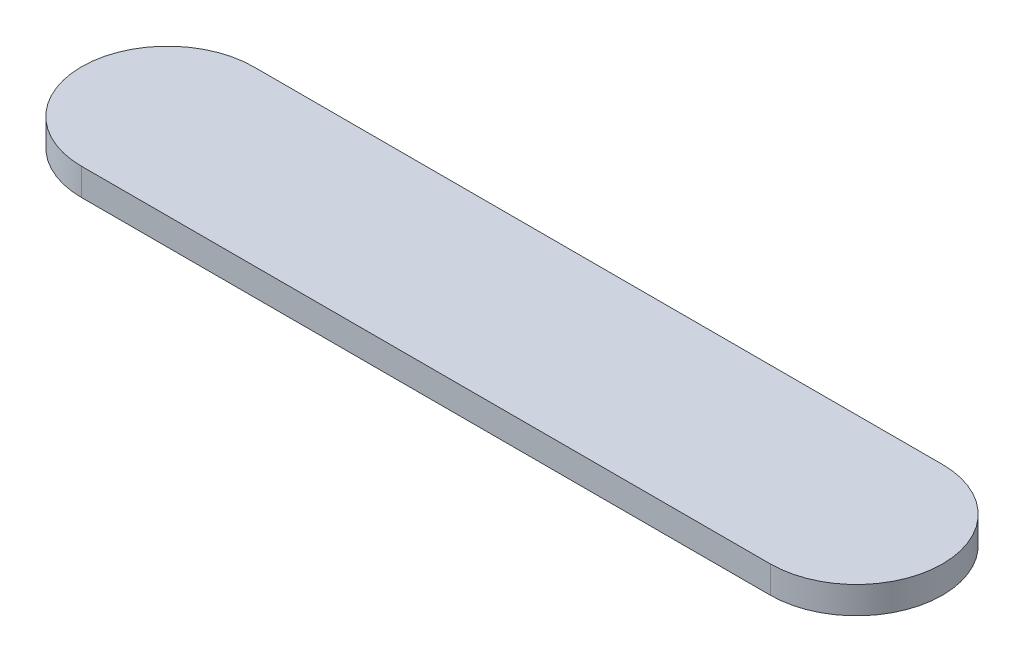
SolidWorks part; units mm, degrees
ref_plane "Front Plane" through (0, 0, 0) normal (0, 0, 1) x (1, 0, 0)
ref_plane "Top Plane" through (0, 0, 0) normal (0, 1, 0) x (1, 0, 0)
ref_plane "Right Plane" through (0, 0, 0) normal (1, 0, 0) x (0, 0, -1)
sketch "Sketch1" plane through (0, 0, 0) normal (0, 1, 0) x (1, 0, 0)
  line L1 (-50.8, 12.7) -> (50.8, 12.7)
  line L2 (-50.8, 12.7) -> (-50.8, -12.7) construction
  line L3 (-50.8, -12.7) -> (50.8, -12.7)
  line L4 (50.8, 12.7) -> (50.8, -12.7) construction
  line L5 (-50.8, 12.7) -> (50.8, -12.7) construction
  line L6 (-50.8, -12.7) -> (50.8, 12.7) construction
  arc A0 (-50.8, 12.7) -> (-50.8, -12.7) centre (-50.8, 0) ccw
  arc A1 (50.8, -12.7) -> (50.8, 12.7) centre (50.8, 0) ccw
  point P0 (0, 0)
  dimension "D1" = 101.6
  dimension "D2" = 25.4
extrude "Boss-Extrude1" add sketch "Sketch1" along normal blind 4
